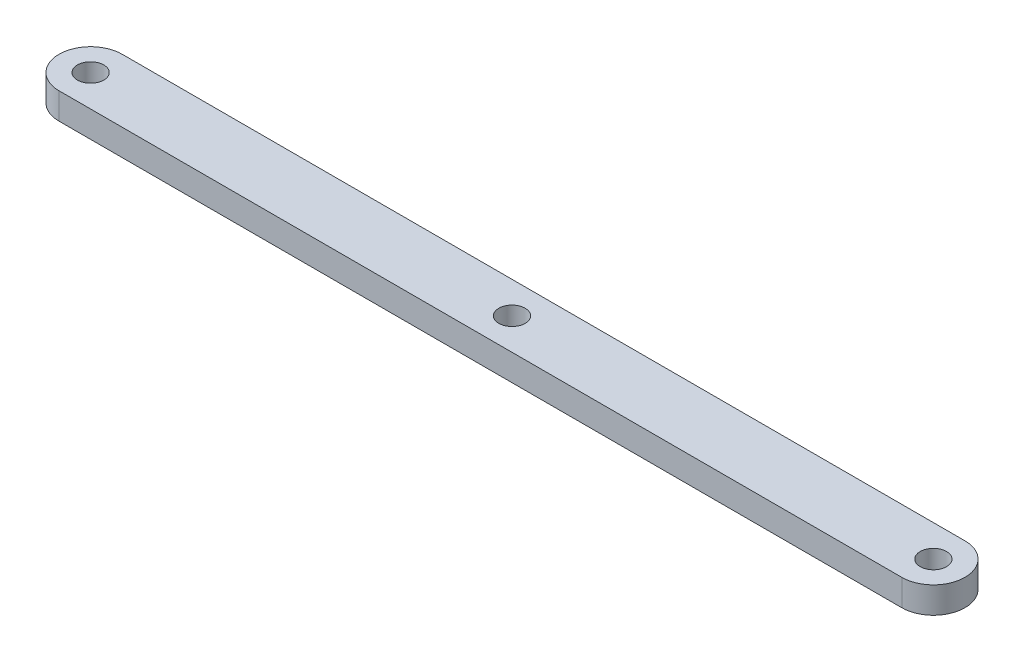
SolidWorks part; units mm, degrees
ref_plane "Front Plane" through (0, 0, 0) normal (0, 0, 1) x (1, 0, 0)
ref_plane "Top Plane" through (0, 0, 0) normal (0, 1, 0) x (1, 0, 0)
ref_plane "Right Plane" through (0, 0, 0) normal (1, 0, 0) x (0, 0, -1)
sketch "Sketch1" plane through (0, 0, 0) normal (0, 1, 0) x (1, 0, 0)
  line L0 (-50.8, 0) -> (50.8, 0)
  line L1 (-50.8, 3.81) -> (50.8, 3.81)
  line L2 (-50.8, -3.81) -> (50.8, -3.81)
  arc A0 (-50.8, 3.81) -> (-50.8, -3.81) centre (-50.8, 0) ccw
  arc A1 (50.8, -3.81) -> (50.8, 3.81) centre (50.8, 0) ccw
  point P4 (0, 0)
  dimension "D2" = 7.62
  dimension "D3" = 7.62
sketch "Sketch3" plane through (0, 0, 0) normal (0, 1, 0) x (1, 0, 0)
  line L0 (-50.8, 3.81) -> (50.8, 3.81)
  line L1 (-50.8, -3.81) -> (50.8, -3.81)
  arc A0 (-50.8, 3.81) -> (-50.8, -3.81) centre (-50.8, 0) ccw
  arc A1 (50.8, -3.81) -> (50.8, 3.81) centre (50.8, 0) ccw
extrude "Boss-Extrude1" add sketch "Sketch3" along normal blind 3.175
sketch "Sketch4" plane through (0, 3.175, 0) normal (0, 1, 0) x (1, 0, 0)
  line L0 (-50.8, 0) -> (50.8, 0) construction
  circle A1 centre (-50.8, 0) radius 1.5875
  circle A2 centre (0, 0) radius 1.5875
  circle A3 centre (50.8, 0) radius 1.5875
  dimension "D1" = 3.175
  dimension "D2" = 3.175
  dimension "D3" = 3.175
extrude "Cut-Extrude1" cut sketch "Sketch4" against normal through all
